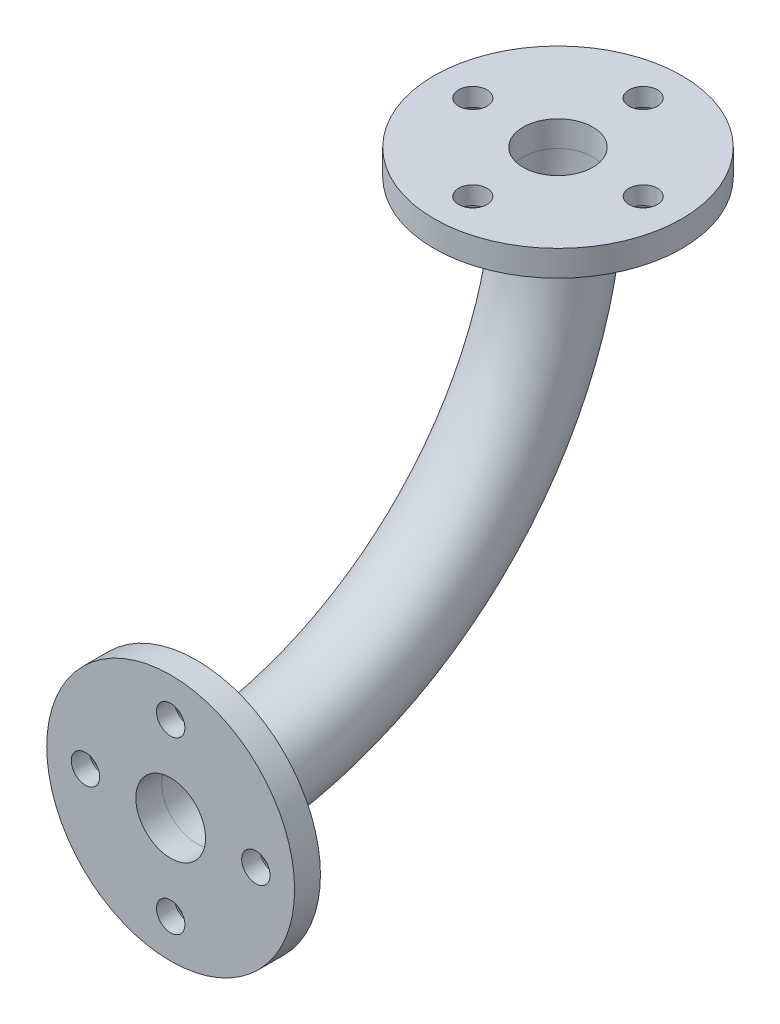
SolidWorks part; units mm, degrees
ref_plane "Alzado" through (0, 0, 0) normal (0, 0, 1) x (1, 0, 0)
ref_plane "Planta" through (0, 0, 0) normal (0, 1, 0) x (1, 0, 0)
ref_plane "Vista lateral" through (0, 0, 0) normal (1, 0, 0) x (0, 0, -1)
sketch "Croquis1" plane through (0, 0, 0) normal (0, 0, 1) x (1, 0, 0)
  line L0 (0, 0) -> (0, 48) construction
  line L1 (0, 0) -> (0, -48) construction
  line L2 (-48, 0) -> (48, 0) construction
  circle A0 centre (0, 0) radius 48
  circle A1 centre (0, 0) radius 13.5
  circle A2 centre (0, 33) radius 5.5 construction
  circle A3 centre (33, 0) radius 5.5 construction
  circle A4 centre (0, -33) radius 5.5 construction
  circle A5 centre (-33, 0) radius 5.5 construction
  point P6 (0, 0)
  point P9 (0, 0)
  point P19 (0, 0)
  dimension "D1" = 96
  dimension "D2" = 27
  dimension "D4" = 11
  dimension "D5" = 4
  dimension "D3" = 33
extrude "Saliente-Extruir1" add sketch "Croquis1" against normal blind 10
sketch "Croquis2" plane through (0, 0, -10) normal (0, 0, -1) x (-1, 0, 0)
  circle A0 centre (0, 0) radius 13.5
  circle A1 centre (0, 0) radius 18
  dimension "D1" = 36
  dimension "D2" = 27
sketch "Croquis3" plane through (0, 0, 0) normal (1, 0, 0) x (0, 0, -1)
  line L0 (10, -18) -> (10, 18) construction
  arc A0 (10, 0) -> (150, 140) centre (10, 140) ccw
  dimension "D1" = 140
sweep "Barrer1" add profiles "Croquis2" path "Croquis3"
sketch "Croquis4" plane through (0, 0, -10) normal (0, 0, -1) x (-1, 0, 0)
  circle A0 centre (0, 33) radius 5.5 construction
  circle A1 centre (0, 33) radius 5.5 construction
  circle A2 centre (33, 0) radius 5.5 construction
  circle A4 centre (33, 0) radius 5.5 construction
  circle A5 centre (0, -33) radius 5.5 construction
  circle A6 centre (0, -33) radius 5.5 construction
  circle A8 centre (-33, 0) radius 5.5 construction
  circle A9 centre (-33, 0) radius 5.5 construction
hole_wizard "Taladro1" positions "Croquis6" profile "Croquis7" legacy end condition through all
sketch "Croquis6" plane through (0, 0, -10) normal (0, 0, -1) x (-1, 0, 0)
  point P0 (0, 33)
  point P3 (33, 0)
  point P6 (0, -33)
  point P9 (-33, 0)
sketch "Croquis7" plane through (0, 33, -10) normal (1, 0, 0) x (0, 1, 0)
  line L0 (0, 0) -> (0, 13.3047)
  line L1 (0, 13.3047) -> (5.5, 10)
  line L2 (5.5, 10) -> (5.5, 3)
  line L3 (5.5, 3) -> (9, 3)
  line L4 (9, 0) -> (0, 0)
  line L5 (0, -11.3109) -> (0, 121.1557) construction
  line L6 (0, 13.3047) -> (-5.5, 10) construction
  line L7 (9, 3) -> (9, 0)
  dimension "Diámetro" = 11
  dimension "Profundidad" = 10
  dimension "Diámetro de refrentado 1" = 18
  dimension "Profundidad de refrentado 1" = 3
  dimension "Ángulo de perforado" = 118
sketch "Croquis8" plane through (0, 140, 0) normal (0, 1, 0) x (1, 0, 0)
  line L0 (0, 10) -> (0, 150) construction
  circle A0 centre (0, 150) radius 48
  circle A1 centre (0, 150) radius 13.5
  circle A3 centre (0, 150) radius 13.5 construction
  dimension "D1" = 96
extrude "Saliente-Extruir3" add sketch "Croquis8" along normal blind 10
sketch "Croquis9" plane through (0, 140, 0) normal (0, -1, 0) x (1, 0, 0)
  circle A0 centre (0, -117) radius 5.5 construction
  circle A1 centre (33, -150) radius 5.5 construction
  circle A2 centre (0, -183) radius 5.5 construction
  circle A3 centre (-33, -150) radius 5.5 construction
  point P12 (0, -150)
  dimension "D2" = 11
  dimension "D1" = 33
  dimension "D3" = 4
hole_wizard "Taladro2" positions "Croquis10" profile "Croquis11" legacy end condition through all
sketch "Croquis10" plane through (0, 140, 0) normal (0, -1, 0) x (-1, 0, 0)
  point P0 (0, 117)
  point P3 (33, 150)
  point P6 (0, 183)
  point P9 (-33, 150)
sketch "Croquis11" plane through (0, 140, -117) normal (1, 0, 0) x (0, 0, -1)
  line L0 (0, 0) -> (0, 13.3047)
  line L1 (0, 13.3047) -> (5.5, 10)
  line L2 (5.5, 10) -> (5.5, 3)
  line L3 (5.5, 3) -> (9, 3)
  line L4 (9, 0) -> (0, 0)
  line L5 (0, -11.3109) -> (0, 121.1557) construction
  line L6 (0, 13.3047) -> (-5.5, 10) construction
  line L7 (9, 3) -> (9, 0)
  dimension "Diámetro" = 11
  dimension "Profundidad" = 10
  dimension "Diámetro de refrentado 1" = 18
  dimension "Profundidad de refrentado 1" = 3
  dimension "Ángulo de perforado" = 118
